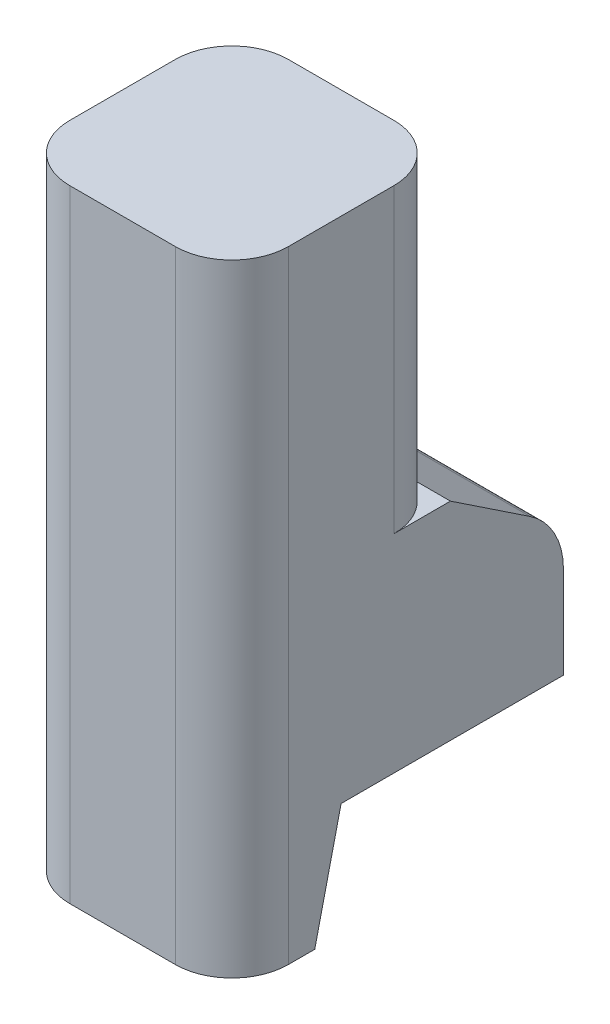
SolidWorks part; units mm, degrees
ref_plane "正面" through (0, 0, 0) normal (0, 0, 1) x (1, 0, 0)
ref_plane "平面" through (0, 0, 0) normal (0, 1, 0) x (1, 0, 0)
ref_plane "右側面" through (0, 0, 0) normal (1, 0, 0) x (0, 0, -1)
sketch "ｽｹｯﾁ1" plane through (0, 0, 0) normal (0, 1, 0) x (1, 0, 0)
  line L0 (2.9, 5.8) -> (2.9, 0) construction
  line L1 (0, 0) -> (5.8, 0)
  line L2 (0, 0) -> (0, 5.8)
  line L3 (0, 5.8) -> (5.8, 5.8)
  line L4 (5.8, 0) -> (5.8, 5.8)
  line L5 (0, 2.9) -> (5.8, 2.9) construction
  circle A0 centre (2.9, 2.9) radius 1.7
  dimension "D3" = 3.4
  dimension "D1" = 5.8
  dimension "D2" = 5.8
sketch "ｽｹｯﾁ2" plane through (0, 0, 0) normal (0, 1, 0) x (1, 0, 0)
  line L0 (0, 0) -> (0, 5.8) construction
  line L1 (5.8, 5.8) -> (0, 5.8)
  line L2 (5.8, 5.8) -> (5.8, -3)
  line L3 (5.8, -3) -> (0, -3)
  line L4 (0, 5.8) -> (0, -3)
  line L5 (0, 0) -> (5.8, 0) construction
  dimension "D1" = 3
extrude "ﾎﾞｽ - 押し出し1" add sketch "ｽｹｯﾁ2" along normal blind 16.5
sketch "ｽｹｯﾁ3" plane through (0, 0, 0) normal (0, -1, 0) x (1, 0, 0)
  line L0 (5.8, 3) -> (5.8, -5.8) construction
  line L1 (0, -5.8) -> (5.8, -5.8)
  line L2 (0, -5.8) -> (0, 0.1)
  line L3 (0, 0.1) -> (5.8, 0.1)
  line L4 (5.8, -5.8) -> (5.8, 0.1)
  line L5 (0, 0) -> (5.8, 0) construction
  dimension "D1" = 0.1
extrude "ｶｯﾄ - 押し出し1" cut sketch "ｽｹｯﾁ3" against normal blind 3
sketch "ｽｹｯﾁ4" plane through (0, 3, 0) normal (0, -1, 0) x (1, 0, 0)
  circle A0 centre (2.9, -2.9) radius 1.75
  dimension "D1" = 3.5
extrude "ｶｯﾄ - 押し出し2" cut sketch "ｽｹｯﾁ4" against normal blind 2.5
sketch "ｽｹｯﾁ5" plane through (0, 16.5, 0) normal (0, 1, 0) x (1, 0, 0)
  line L0 (5.8, 0) -> (5.8, 5.8) construction
  line L1 (0, 5.8) -> (5.8, 5.8)
  line L2 (0, 5.8) -> (0, 2.8)
  line L3 (0, 2.8) -> (5.8, 2.8)
  line L4 (5.8, 5.8) -> (5.8, 2.8)
  line L5 (0, -3) -> (5.8, -3) construction
  dimension "D1" = 5.8
extrude "ｶｯﾄ - 押し出し3" cut sketch "ｽｹｯﾁ5" against normal blind 8
fillet "ﾌｨﾚｯﾄ1" radius 1.5 4 edges at (0, 8.25, 3) (5.8, 8.25, 3) (5.8, 12.5, -2.8) (0, 12.5, -2.8)
sketch "ｽｹｯﾁ6" plane through (0, 16.5, 0) normal (0, 1, 0) x (1, 0, 0)
  line L0 (2.9, 2.8) -> (2.9, -3) construction
  line L1 (1.5, 2.8) -> (4.3, 2.8) construction
  line L2 (1.5, -3) -> (4.3, -3) construction
  line L3 (0, -0.1) -> (5.8, -0.1) construction
  line L4 (5.8, -1.5) -> (5.8, 1.3) construction
sketch "ｽｹｯﾁ9" plane through (5.8, 0, 0) normal (1, 0, 0) x (0, 0, -1)
  line L0 (5.8, 8.5) -> (5.8, 3) construction
  line L1 (2.8, 8.5) -> (5.8, 6.5)
  dimension "D1" = 2
extrude "ｶｯﾄ - 押し出し4" cut sketch "ｽｹｯﾁ9" against normal through all and the other way through all
fillet "ﾌｨﾚｯﾄ2" radius 2 1 edges at (2.9, 6.5, -5.8)
sketch "ｽｹｯﾁ10" plane through (5.8, 0, 0) normal (1, 0, 0) x (0, 0, -1)
  line L0 (-0.1, 3) -> (-0.8, 0)
  line L1 (-1.5, 0) -> (-0.1, 0) construction
extrude "ｶｯﾄ - 押し出し5" cut sketch "ｽｹｯﾁ10" against normal through all and the other way through all
